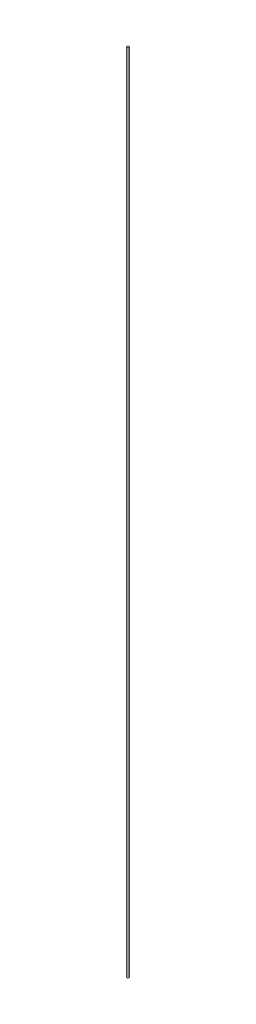
SolidWorks part; units mm, degrees
material "Alloy Steel"
ref_plane "Front Plane" through (0, 0, 0) normal (0, 0, 1) x (1, 0, 0)
ref_plane "Top Plane" through (0, 0, 0) normal (0, 1, 0) x (1, 0, 0)
ref_plane "Right Plane" through (0, 0, 0) normal (1, 0, 0) x (0, 0, -1)
sketch "Sketch1" plane through (0, 0, 0) normal (0, 1, 0) x (1, 0, 0)
  circle A0 centre (0, 0) radius 0.5
  dimension "D1" = 1
extrude "Antenna" add sketch "Sketch1" along normal blind 445
